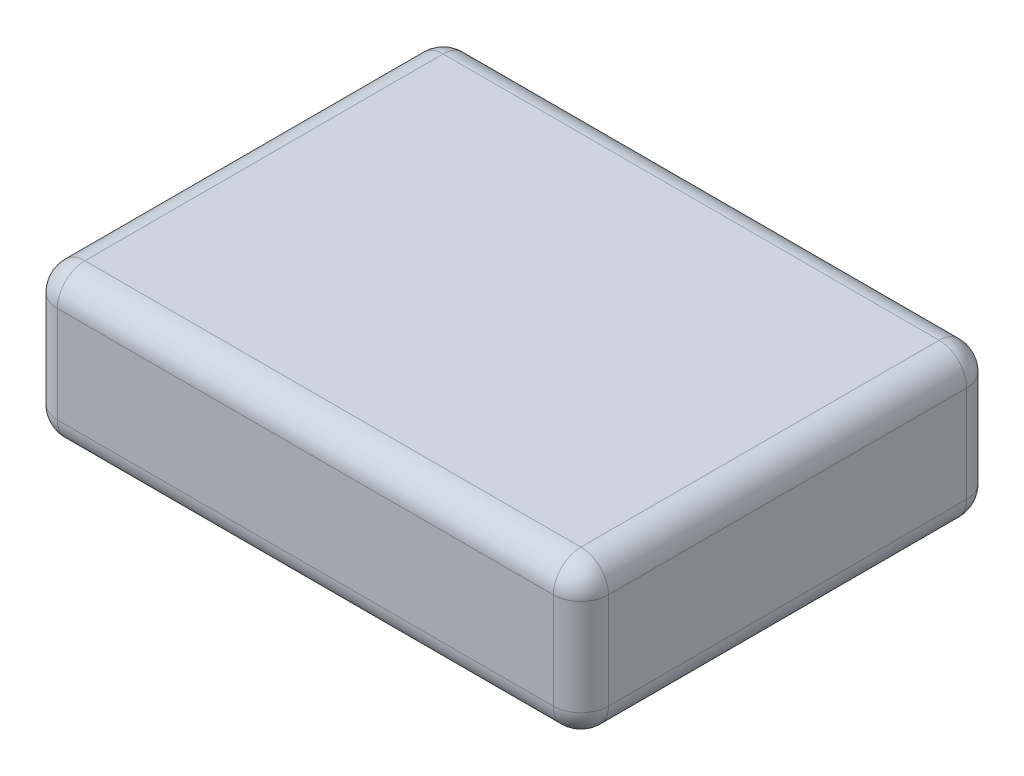
SolidWorks part; units mm, degrees
ref_plane "前视基准面" through (0, 0, 0) normal (0, 0, 1) x (1, 0, 0)
ref_plane "上视基准面" through (0, 0, 0) normal (0, 1, 0) x (1, 0, 0)
ref_plane "右视基准面" through (0, 0, 0) normal (1, 0, 0) x (0, 0, -1)
sketch "草图1" plane through (0, 0, 0) normal (0, 1, 0) x (1, 0, 0)
  line L1 (0, 0) -> (40, 0)
  line L2 (0, 0) -> (0, 30)
  line L3 (0, 30) -> (40, 30)
  line L4 (40, 0) -> (40, 30)
  dimension "D1" = 30
  dimension "D2" = 40
extrude "凸台-拉伸1" add sketch "草图1" along normal blind 11
fillet "圆角1" radius 2 12 edges at (40, 0, -15) (40, 5.5, -30) (20, 0, -30) (0, 5.5, -30) (0, 0, -15) (20, 11, -30) (40, 11, -15) (0, 11, -15) (0, 5.5, 0) (20, 11, 0) (40, 5.5, 0) (20, 0, 0)
